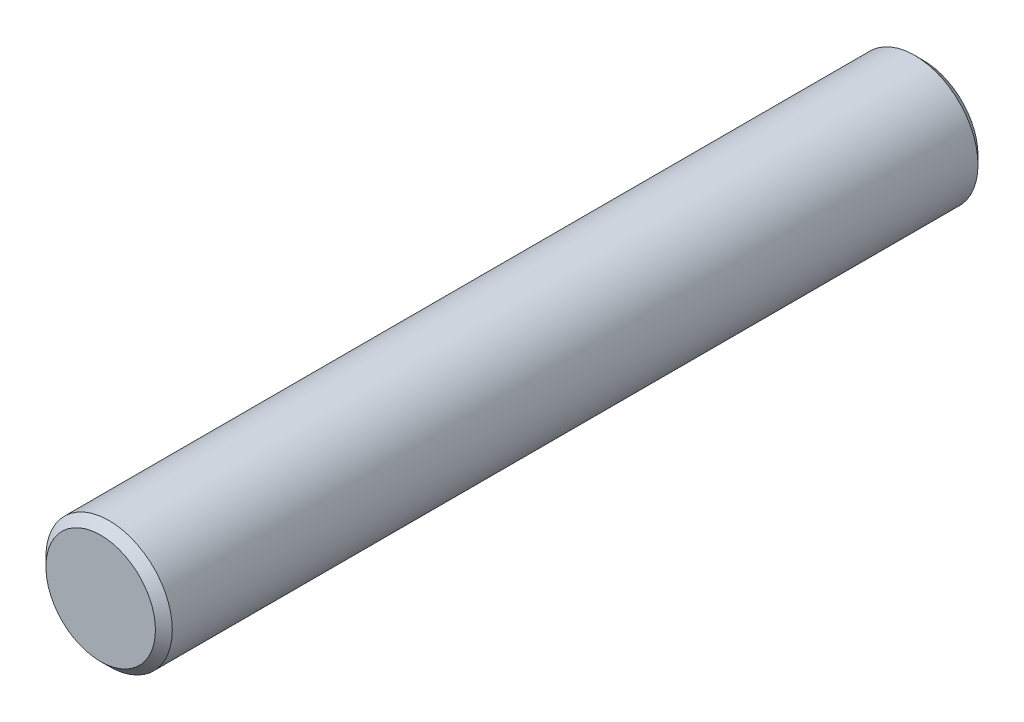
SolidWorks part; units mm, degrees
ref_plane "Front Plane" through (0, 0, 0) normal (0, 0, 1) x (1, 0, 0)
ref_plane "Top Plane" through (0, 0, 0) normal (0, 1, 0) x (1, 0, 0)
ref_plane "Right Plane" through (0, 0, 0) normal (1, 0, 0) x (0, 0, -1)
sketch "Sketch1" plane through (0, 0, 0) normal (0, 0, 1) x (1, 0, 0)
  circle A1 centre (0, 114.2609) radius 3.81
extrude "Extrude1" add sketch "Sketch1" against normal blind 49.5881
chamfer "Chamfer1" distance 0.508 angle 45 2 edges at (3.81, 114.2609, -49.5881) (3.81, 114.2609, 0)
